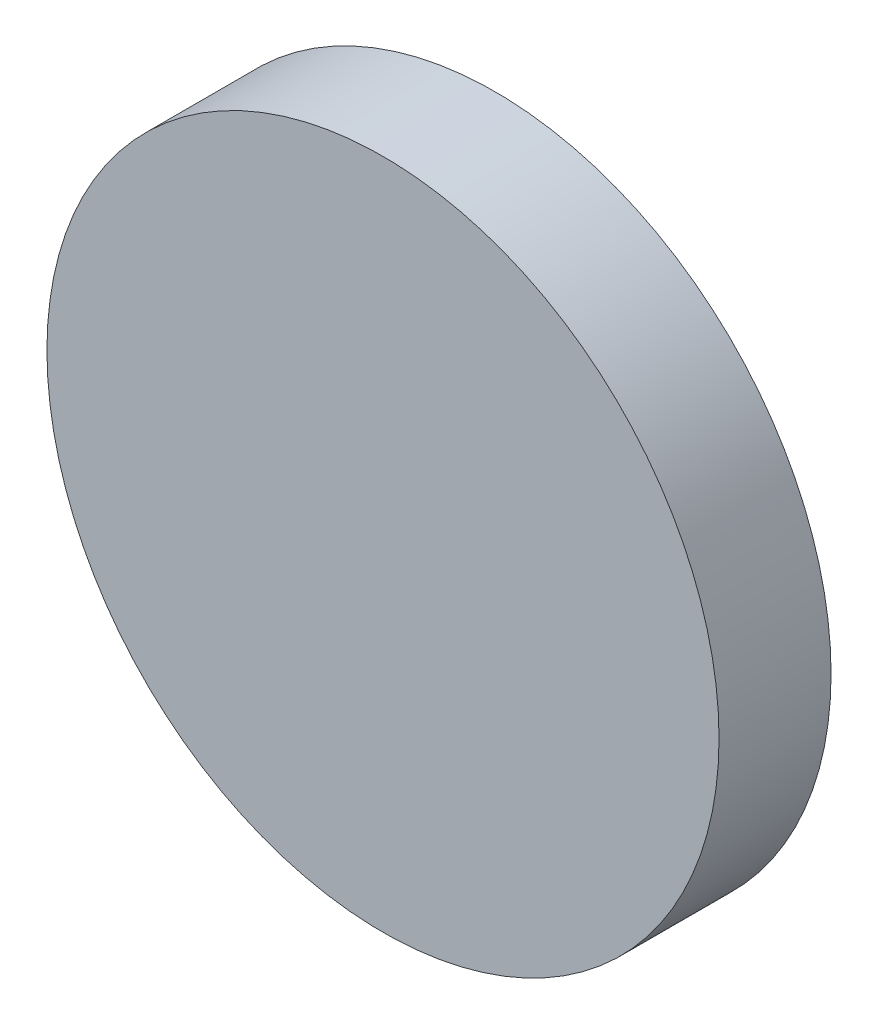
SolidWorks part; units mm, degrees
material "Acciaio al carbonio semplice"
ref_plane "Piano frontale" through (0, 0, 0) normal (0, 0, 1) x (1, 0, 0)
ref_plane "Piano superiore" through (0, 0, 0) normal (0, 1, 0) x (1, 0, 0)
ref_plane "Piano destro" through (0, 0, 0) normal (1, 0, 0) x (0, 0, -1)
other "Centro di massa"
sketch "Schizzo1" plane through (0, 0, 0) normal (0, 0, 1) x (1, 0, 0)
  circle A0 centre (0, 0) radius 150
extrude "Estrusione-Estrusione1" add sketch "Schizzo1" against normal blind 50
